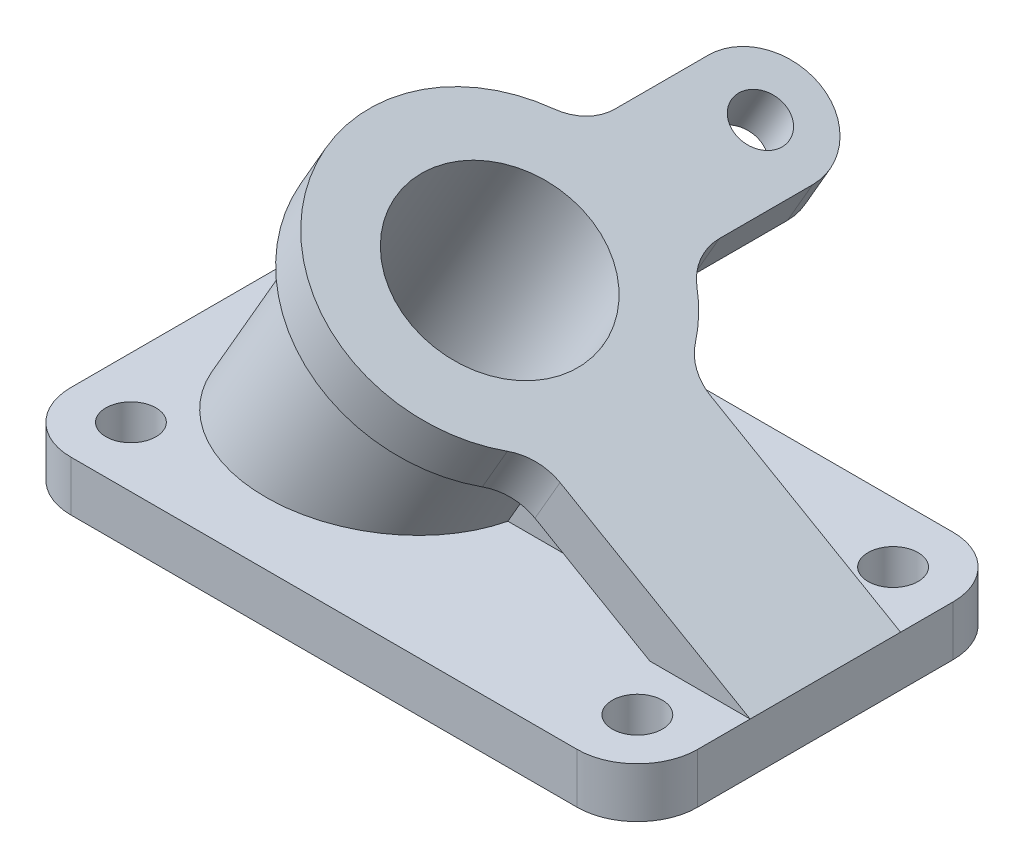
SolidWorks part; units mm, degrees
ref_plane "前视基准面" through (0, 0, 0) normal (0, 0, 1) x (1, 0, 0)
ref_plane "上视基准面" through (0, 0, 0) normal (0, 1, 0) x (1, 0, 0)
ref_plane "右视基准面" through (0, 0, 0) normal (1, 0, 0) x (0, 0, -1)
other "Configuration Table"
sketch "草图1" plane through (0, 0, 0) normal (0, 1, 0) x (1, 0, 0)
  line L1 (-50.5, 37.5) -> (50.5, 37.5)
  line L2 (-62.5, 25.5) -> (-62.5, -25.5)
  line L3 (-50.5, -37.5) -> (50.5, -37.5)
  line L4 (62.5, 25.5) -> (62.5, -25.5)
  line L5 (-62.5, 37.5) -> (62.5, -37.5) construction
  line L6 (-62.5, -37.5) -> (62.5, 37.5) construction
  arc A0 (50.5, 37.5) -> (62.5, 25.5) centre (50.5, 25.5) cw
  arc A1 (-62.5, -25.5) -> (-50.5, -37.5) centre (-50.5, -25.5) ccw
  arc A2 (-50.5, 37.5) -> (-62.5, 25.5) centre (-50.5, 25.5) ccw
  arc A3 (50.5, -37.5) -> (62.5, -25.5) centre (50.5, -25.5) ccw
  circle A4 centre (50.5, -25.5) radius 5
  circle A5 centre (50.5, 25.5) radius 5
  circle A6 centre (-50.5, 25.5) radius 5
  circle A7 centre (-50.5, -25.5) radius 5
  point P0 (0, 0)
  dimension "D3" = 12
  dimension "D4" = 12
  dimension "D5" = 12
  dimension "D6" = 12
  dimension "D7" = 10
  dimension "D1" = 125
  dimension "D2" = 75
extrude "凸台-拉伸1" add sketch "草图1" along normal blind 10
ref_plane "基准面1" through (19.9551, 34.5633, 0) normal (0.5, 0.866, 0) x (0, 0, -1)
sketch "草图3" plane through (19.9551, 34.5633, 0) normal (0.5, 0.866, 0) x (0, 0, -1)
  line L0 (0, -49.1266) -> (0, 150.4183) construction
  line L2 (-25.5, -49.1266) -> (25.5, -49.1266) construction
  line L3 (-15, -49.1266) -> (15, -49.1266)
  line L4 (15, -49.1266) -> (15, -5.3516)
  line L5 (-15, -49.1266) -> (-15, -5.3516)
  line L6 (0, 25.8734) -> (95.329, 25.8734) construction
  line L7 (52, 37.8734) -> (33.4066, 37.8734)
  line L8 (52, 13.8734) -> (33.4066, 13.8734)
  circle A1 centre (0, 25.8734) radius 25
  arc A2 (25.0549, 42.3734) -> (-18.75, 2.4547) centre (0, 25.8734) ccw
  arc A3 (52, 13.8734) -> (52, 37.8734) centre (52, 25.8734) ccw
  circle A4 centre (52, 25.8734) radius 5
  arc A5 (18.75, 2.4547) -> (25.0549, 9.3734) centre (0, 25.8734) ccw
  arc A6 (-15, -5.3516) -> (-18.75, 2.4547) centre (-25, -5.3516) ccw
  arc A7 (15, -5.3516) -> (18.75, 2.4547) centre (25, -5.3516) cw
  arc A8 (33.4066, 37.8734) -> (25.0549, 42.3734) centre (33.4066, 47.8734) cw
  arc A9 (33.4066, 13.8734) -> (25.0549, 9.3734) centre (33.4066, 3.8734) ccw
  point P15 (-15, -0.1073)
  point P23 (15, -0.1073)
  dimension "D1" = 10
  dimension "D2" = 50
  dimension "D3" = 60
  dimension "D6" = 24
  dimension "D7" = 10
  dimension "D9" = 10
  dimension "D10" = 10
  dimension "D11" = 10
  dimension "D4" = 15
  dimension "D5" = 75
  dimension "D8" = 52
extrude "凸台-拉伸4" add sketch "草图3" against normal blind 10
sketch "草图11" plane through (19.9551, 34.5633, 0) normal (0.5, 0.866, 0) x (0.866, -0.5, 0)
  circle A0 centre (-25.8734, 0) radius 25
extrude "凸台-拉伸5" add sketch "草图11" against normal up to surface (57.735 mm away)
sketch "草图13" plane through (19.9551, 34.5633, 0) normal (0.5, 0.866, 0) x (0, 0, -1)
  circle A0 centre (0, 25.8734) radius 18
  arc A1 (25.0549, 42.3734) -> (-18.75, 2.4547) centre (0, 25.8734) ccw construction
  dimension "D1" = 36
extrude "切除-拉伸5" cut sketch "草图13" against normal through all both and the other way through all
sketch "草图14" plane through (0, 0, 0) normal (0, 0, 1) x (1, 0, 0)
  line L0 (14.1987, 26.3397) -> (42.5, 10)
rib "筋2" sketch "草图14" sketch "草图14" thickness 10 extrusion direction parallel to sketch draft on no parameters "D1"=10
sketch "草图15" plane through (0, 0, 0) normal (0, -1, 0) x (1, 0, 0)
  line L6 (-41.458, 25.5) -> (41.458, 25.5)
  line L8 (-50.5, 16.458) -> (-50.5, -16.458)
  line L9 (-41.458, -25.5) -> (41.458, -25.5)
  line L10 (50.5, 16.458) -> (50.5, -16.458)
  line L11 (-42.4286, 21.4244) -> (42.4286, -21.4244) construction
  line L12 (-42.4286, -21.4244) -> (42.4286, 21.4244) construction
  circle A0 centre (-50.5, 25.5) radius 5 construction
  arc A2 (-50.5, 16.458) -> (-41.458, 25.5) centre (-50.5, 25.5) ccw
  arc A3 (-41.458, -25.5) -> (-50.5, -16.458) centre (-50.5, -25.5) ccw
  arc A4 (50.5, -16.458) -> (41.458, -25.5) centre (50.5, -25.5) ccw
  arc A5 (41.458, 25.5) -> (50.5, 16.458) centre (50.5, 25.5) ccw
  point P0 (0, 0)
  point P1 (0, 0)
extrude "切除-拉伸6" cut sketch "草图15" against normal blind 5 and the other way through all
sketch "草图16" plane through (19.9551, 34.5633, 0) normal (0.5, 0.866, 0) x (0.866, -0.5, 0)
  line L0 (-25.8734, -30) -> (-25.8734, 3.3718)
  arc A0 (-42.3734, 25.0549) -> (-2.4547, -18.75) centre (-25.8734, 0) ccw construction
ref_plane "基准面2" through (-22.407, 12.9367, 0) normal (0.866, -0.5, 0) x (0, 0, -1)
sketch "草图18" plane through (-22.407, 12.9367, 0) normal (0.866, -0.5, 0) x (0, 0, -1)
  line L0 (42, 29.9103) -> (25, 2.9103)
  line L1 (52, 29.9103) -> (33.4066, 29.9103) construction
  line L2 (25, -3.391) -> (25, 29.9103) construction
  line L3 (52, 29.9103) -> (52, 39.9103) construction
  dimension "D1" = 10
  dimension "D2" = 27
rib "筋3" sketch "草图18" sketch "草图18" thickness 10 extrusion direction parallel to sketch draft on no parameters "D1"=10
